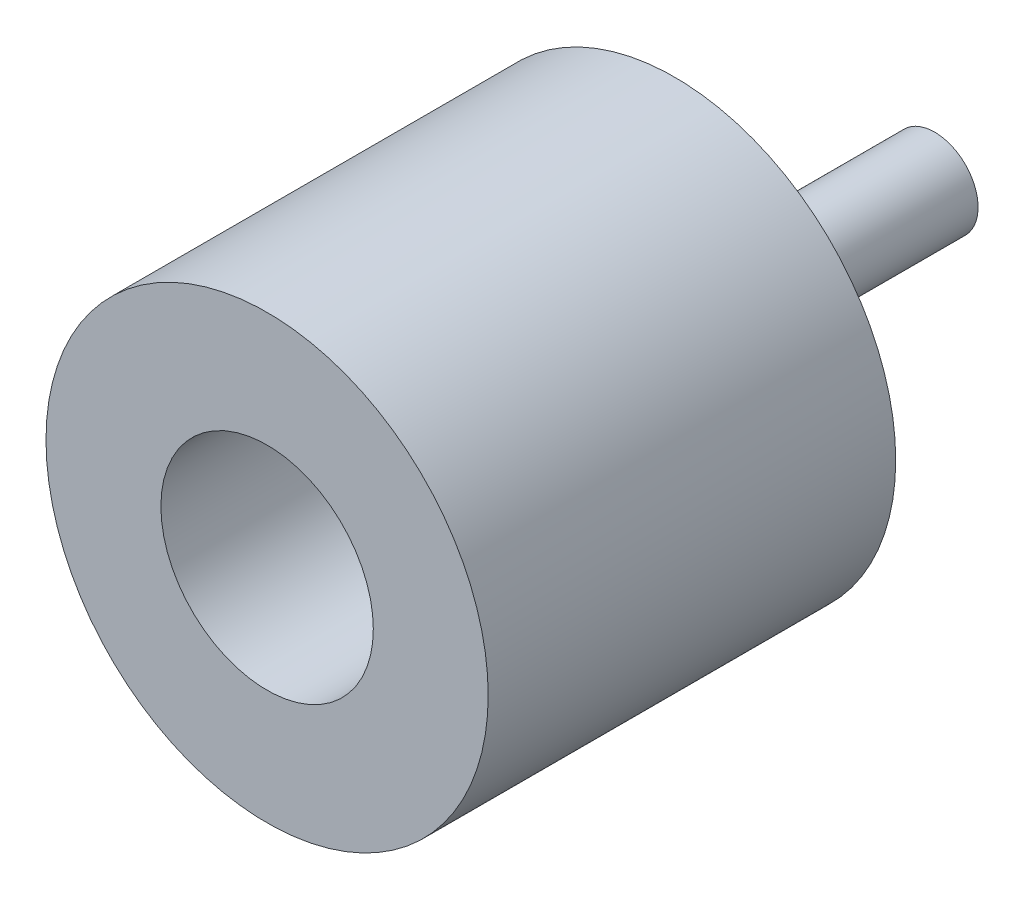
SolidWorks part; units mm, degrees
ref_plane "Front Plane" through (0, 0, 0) normal (0, 0, 1) x (1, 0, 0)
ref_plane "Top Plane" through (0, 0, 0) normal (0, 1, 0) x (1, 0, 0)
ref_plane "Right Plane" through (0, 0, 0) normal (1, 0, 0) x (0, 0, -1)
sketch "Sketch2" plane through (0, 0, 0) normal (0, 1, 0) x (1, 0, 0)
  line L0 (1.225, -0.2) -> (2.55, -0.2)
  line L1 (2.55, -0.2) -> (2.55, 4.5)
  line L2 (2.55, 4.5) -> (0.5, 4.5)
  line L3 (0.5, 4.5) -> (0.5, 7.5)
  line L4 (0.5, 7.5) -> (0, 7.5)
  line L5 (0, 7.5) -> (0, 3.5)
  line L6 (0, 3.5) -> (1.225, 3.5)
  line L7 (1.225, 3.5) -> (1.225, -0.2)
  line L8 (0, 5.3605) -> (0, 0.5197) construction
revolve "Revolve1" add sketch "Sketch2" angle 360 about L8
